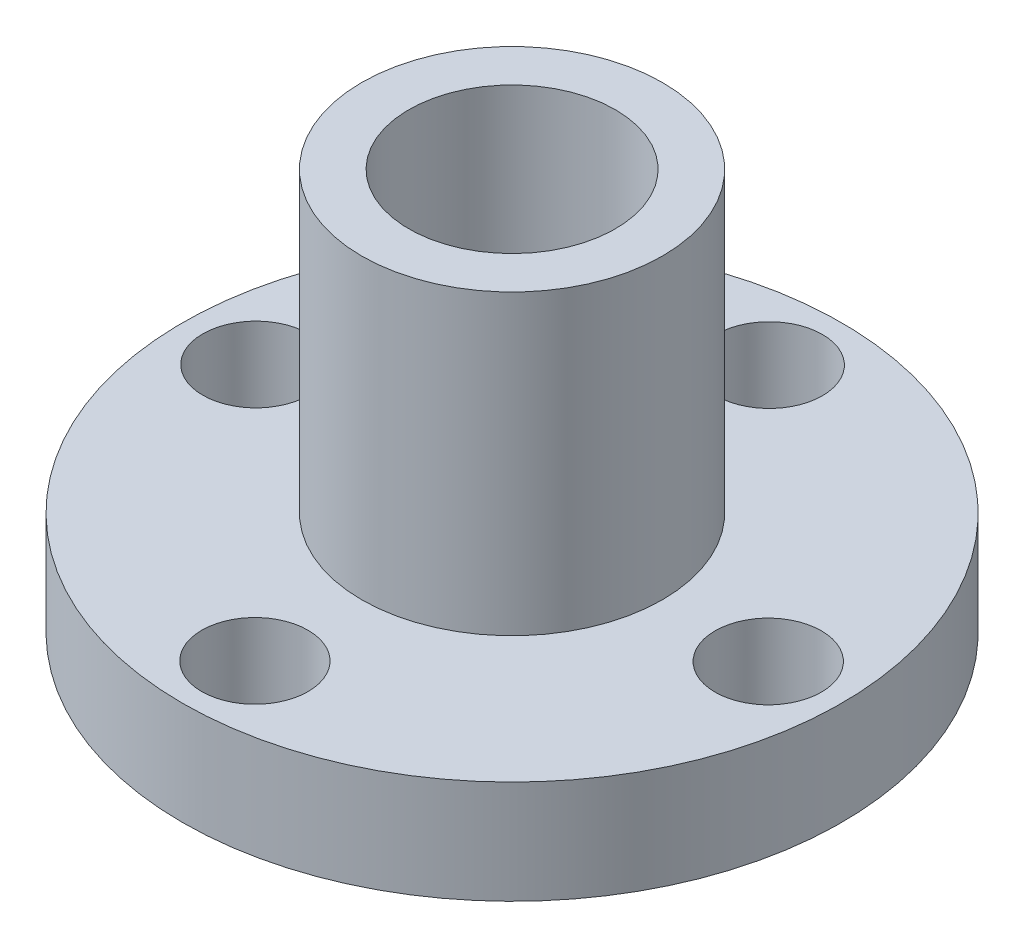
SolidWorks part; units mm, degrees
ref_plane "Front Plane" through (0, 0, 0) normal (0, 0, 1) x (1, 0, 0)
ref_plane "Top Plane" through (0, 0, 0) normal (0, 1, 0) x (1, 0, 0)
ref_plane "Right Plane" through (0, 0, 0) normal (1, 0, 0) x (0, 0, -1)
sketch "Sketch1" plane through (0, 0, 0) normal (0, 1, 0) x (1, 0, 0)
  circle A0 centre (0, 0) radius 5
  dimension "D1" = 10
extrude "Boss-Extrude1" add sketch "Sketch1" along normal blind 1.5
sketch "Sketch2" plane through (0, 1.5, 0) normal (0, 1, 0) x (1, 0, 0)
  circle A0 centre (0, 0) radius 10.85
  dimension "D1" = 21.7
extrude "Boss-Extrude2" add sketch "Sketch2" along normal blind 3.4
sketch "Sketch3" plane through (0, 4.9, 0) normal (0, 1, 0) x (1, 0, 0)
  circle A0 centre (0, 0) radius 4.95
  dimension "D1" = 9.9
extrude "Boss-Extrude3" add sketch "Sketch3" along normal blind 9.8
hole_wizard "M8 Tapped Hole1" positions "3DSketch2" profile "Sketch5" tap size "M8" standard "ISO" end condition through all
sketch3d "3DSketch2"
  point P0 (0, 0, 0)
  point P4 (0, 0, 0)
sketch "Sketch5" plane through (0, 0, 0) normal (1, 0, 0) x (0, 0, -1)
  line L0 (0, 0) -> (0, 14.7)
  line L1 (0, 14.7) -> (3.4, 14.7)
  line L2 (3.4, 14.7) -> (3.4, 0.625)
  line L3 (3.4, 0.625) -> (4.025, 0)
  line L5 (4.025, 0) -> (0, 0)
  line L6 (-3.4, 0.625) -> (-4.025, 0) construction
  line L11 (0, -6.35) -> (0, 107.95) construction
  dimension "Thru Tap Drill Dia." = 6.8
  dimension "Thru Tap Drill Depth" = 14.7
  dimension "Near C'Sink Dia." = 8.05
  dimension "Near C'Sink Angle" = 90
cosmetic thread "Hole Thread1" parameters "D2"=8
sketch "Sketch6" plane through (0, 1.5, 0) normal (0, -1, 0) x (1, 0, 0)
  line L0 (0, 10.85) -> (0.4575, 10.8404) construction
  circle A0 centre (-0.0164, 8.4498) radius 1.75
  circle A3 centre (8.4498, 0.0164) radius 1.75
  circle A4 centre (0.0164, -8.4498) radius 1.75
  circle A5 centre (-8.4498, -0.0164) radius 1.75
  point P13 (0, 0)
  dimension "D1" = 3.5
  dimension "D2" = 2.4
  dimension "D3" = 4
extrude "Cut-Extrude1" cut sketch "Sketch6" against normal through all
